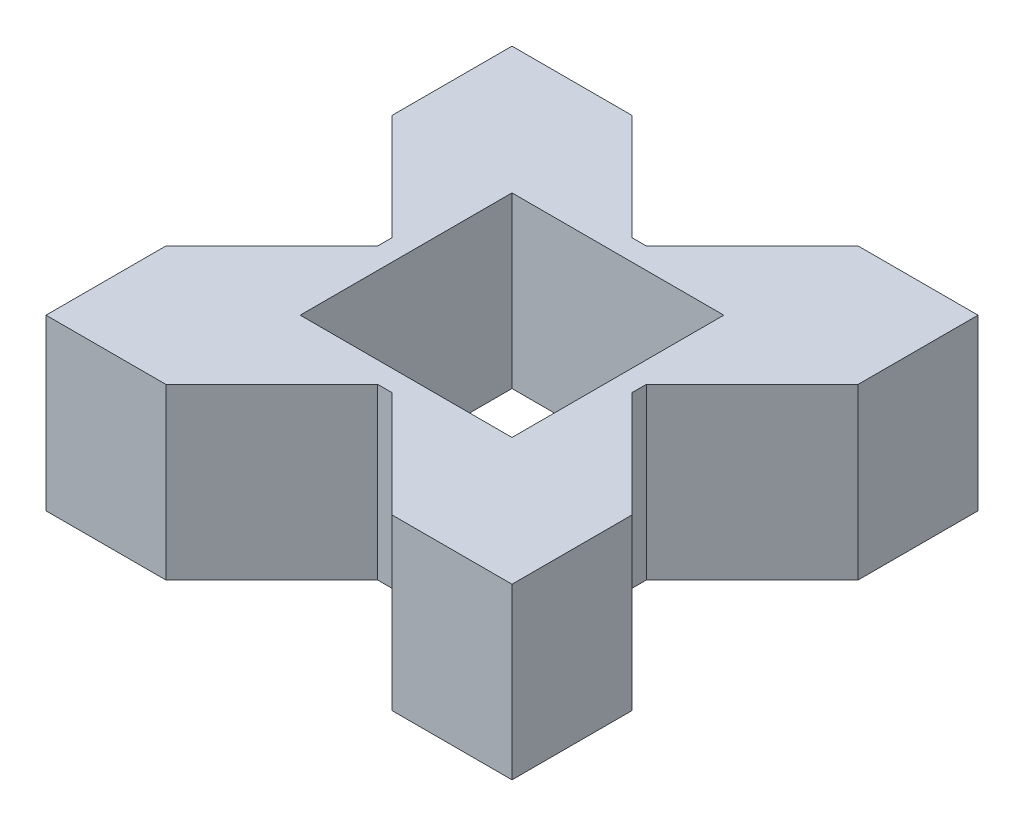
SolidWorks part; units mm, degrees
ref_plane "Front Plane" through (0, 0, 0) normal (0, 0, 1) x (1, 0, 0)
ref_plane "Top Plane" through (0, 0, 0) normal (0, 1, 0) x (1, 0, 0)
ref_plane "Right Plane" through (0, 0, 0) normal (1, 0, 0) x (0, 0, -1)
sketch "Sketch1" plane through (0, 0, 0) normal (0, 1, 0) x (1, 0, 0)
  line L0 (27.5, -13.3579) -> (-13.3579, 27.5)
  line L1 (27.5, -27.5) -> (-27.5, -27.5)
  line L2 (27.5, -27.5) -> (27.5, 27.5)
  line L3 (27.5, 27.5) -> (-27.5, 27.5)
  line L4 (-27.5, -27.5) -> (-27.5, 27.5)
  line L5 (27.5, -27.5) -> (-27.5, 27.5) construction
  line L6 (27.5, 27.5) -> (-27.5, -27.5) construction
  line L7 (13.3579, 27.5) -> (-27.5, -13.3579)
  line L8 (13.3579, -27.5) -> (-27.5, 13.3579)
  line L9 (27.5, 13.3579) -> (-13.3579, -27.5)
  line L10 (34.5711, 20.4289) -> (-20.4289, -34.5711) construction
  line L11 (20.4289, 34.5711) -> (-34.5711, -20.4289) construction
  line L12 (20.4289, -34.5711) -> (-34.5711, 20.4289) construction
  line L13 (34.5711, -20.4289) -> (-20.4289, 34.5711) construction
  line L15 (-15, 15) -> (15, 15)
  line L16 (-15, 15) -> (-15, -15)
  line L17 (-15, -15) -> (15, -15)
  line L18 (15, 15) -> (15, -15)
  line L19 (-15, 15) -> (15, -15) construction
  line L20 (-15, -15) -> (15, 15) construction
  point P0 (0, 0)
  point P22 (0, 0)
  dimension "D1" = 55
  dimension "D2" = 55
  dimension "D5" = 30
  dimension "D6" = 30
  dimension "D3" = 10
  dimension "D4" = 10
extrude "Boss-Extrude1" add sketch "Sketch1" along normal blind 20 contours L8 L7 L0 L3 L4 | L9 L2 L3 L7 L0 | L9 L0 L7 L8 | L9 L8 L7 L4 L1 | L0 L9 L8 L1 L2 | L15 L0 L7 | L18 L15 L7 L0 L9 | L15 L16 L8 L7 L0 | L8 L16 L7 | L16 L17 L9 L8 L7 | L18 L0 L9 L8 L17 | L9 L17 L8 | L18 L9 L0
sketch "Sketch2" plane through (0, 20, 0) normal (0, 1, 0) x (1, 0, 0)
  line L1 (-12.5, 12.5) -> (12.5, 12.5)
  line L2 (-12.5, 12.5) -> (-12.5, -12.5)
  line L3 (-12.5, -12.5) -> (12.5, -12.5)
  line L4 (12.5, 12.5) -> (12.5, -12.5)
  line L5 (-12.5, 12.5) -> (12.5, -12.5) construction
  line L6 (-12.5, -12.5) -> (12.5, 12.5) construction
  point P0 (0, 0)
  dimension "D1" = 25
  dimension "D2" = 25
extrude "Cut-Extrude2" cut sketch "Sketch2" against normal through all
